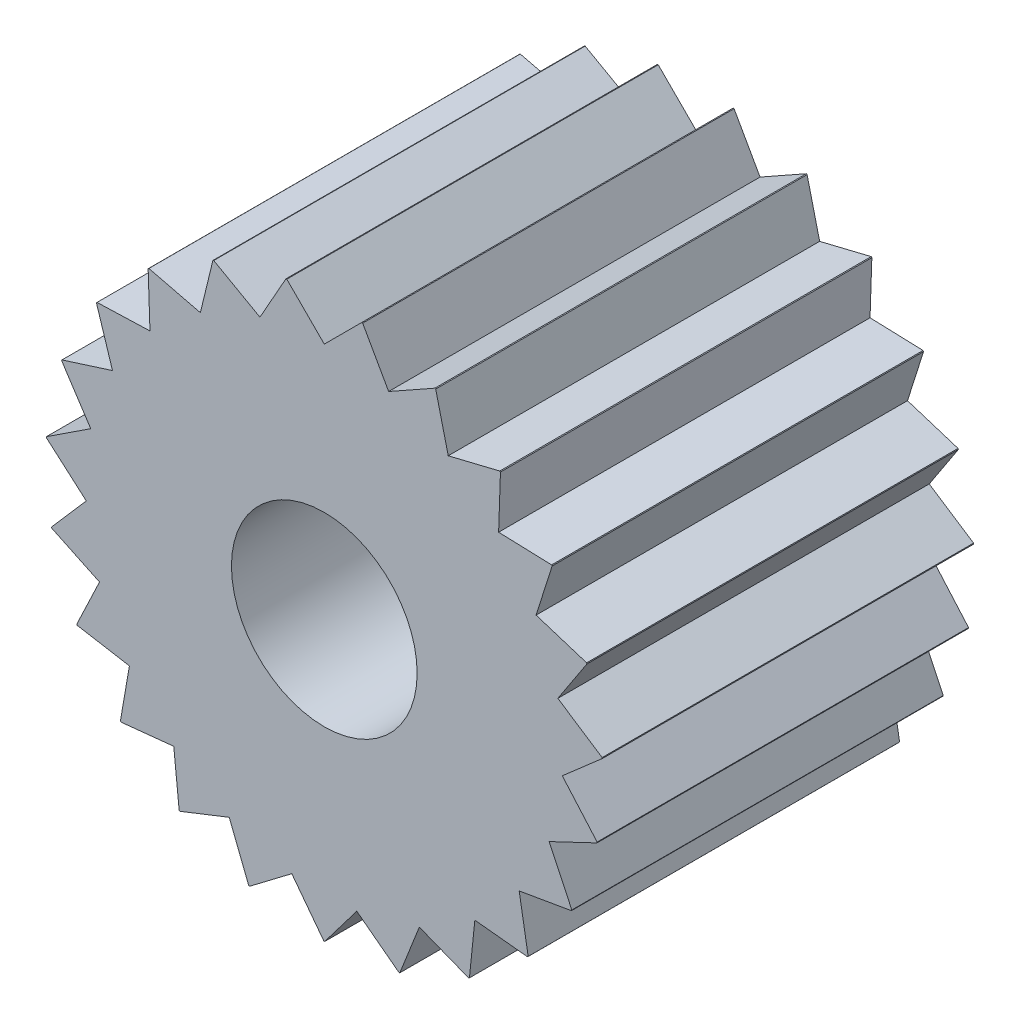
SolidWorks part; units mm, degrees
material "ABS"
ref_plane "Front Plane" through (0, 0, 0) normal (0, 0, 1) x (1, 0, 0)
ref_plane "Top Plane" through (0, 0, 0) normal (0, 1, 0) x (1, 0, 0)
ref_plane "Right Plane" through (0, 0, 0) normal (1, 0, 0) x (0, 0, -1)
sketch "Sketch1" plane through (0, 0, 0) normal (0, 0, 1) x (1, 0, 0)
  circle A0 centre (0, 0) radius 3.75
  circle A1 centre (0, 0) radius 1.25
  dimension "D1" = 2.5
  dimension "D2" = 7.5
extrude "Boss-Extrude1" add sketch "Sketch1" along normal blind 5
sketch "Sketch2" plane through (0, 0, 0) normal (0, 0, 1) x (1, 0, 0)
  line L0 (0, 3.2113) -> (1.0273, 4.2386)
  line L1 (1.0273, 4.2386) -> (-1.0273, 4.2386)
  line L2 (-1.0273, 4.2386) -> (0, 3.2113)
extrude "Cut-Extrude1" cut sketch "Sketch2" along normal through all
pattern_circular "CirPattern1" count 23 over 360 about axis through (0, 0, 0) along (0, 0, 1) of "Cut-Extrude1"
